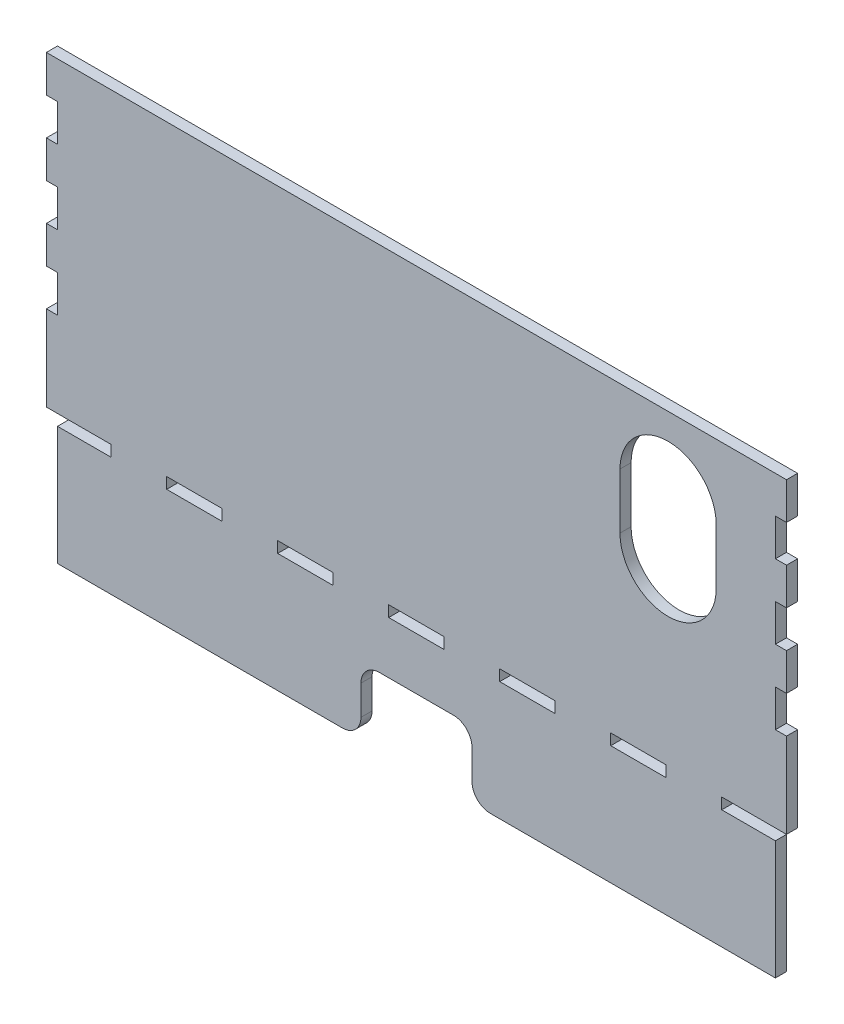
SolidWorks part; units mm, degrees
ref_plane "Front Plane" through (0, 0, 0) normal (0, 0, 1) x (1, 0, 0)
ref_plane "Top Plane" through (0, 0, 0) normal (0, 1, 0) x (1, 0, 0)
ref_plane "Right Plane" through (0, 0, 0) normal (1, 0, 0) x (0, 0, -1)
sketch "Sketch1" plane through (0, 0, 0) normal (0, 0, 1) x (1, 0, 0)
  line L0 (-97, 0) -> (97, 0) construction
  line L1 (0, -25.5) -> (0, 57.5) construction
  line L2 (100, -2.5) -> (97, -2.5)
  line L3 (-97, 57.5) -> (97, 57.5)
  line L4 (100, -25.5) -> (100, -2.5)
  line L5 (0, -25.5) -> (7.5, -25.5)
  line L6 (-97, -25.5) -> (-100, -25.5)
  line L7 (-100, -25.5) -> (-100, -2.5)
  line L8 (-97, 57.5) -> (-100, 57.5)
  line L9 (-100, 57.5) -> (-100, 47.5)
  line L10 (-100, 47.5) -> (-97, 47.5)
  line L11 (-97, 47.5) -> (-97, 37.5)
  line L12 (-97, 37.5) -> (-100, 37.5)
  line L13 (-100, 37.5) -> (-100, 27.5)
  line L14 (100, 17.5) -> (100, 7.5)
  line L15 (-100, 27.5) -> (-97, 27.5)
  line L16 (-97, 27.5) -> (-97, 17.5)
  line L17 (97, 7.5) -> (100, 7.5)
  line L18 (97, 17.5) -> (100, 17.5)
  line L19 (97, 7.5) -> (97, -2.5)
  line L20 (97, 27.5) -> (97, 17.5)
  line L21 (100, 27.5) -> (97, 27.5)
  line L22 (100, 37.5) -> (100, 27.5)
  line L23 (97, 37.5) -> (100, 37.5)
  line L24 (97, 47.5) -> (97, 37.5)
  line L25 (100, 47.5) -> (97, 47.5)
  line L26 (100, 57.5) -> (100, 47.5)
  line L27 (97, 57.5) -> (100, 57.5)
  line L28 (7.5, -25.5) -> (7.5, -28.5)
  line L29 (7.5, -28.5) -> (22.5, -28.5)
  line L30 (22.5, -28.5) -> (22.5, -25.5)
  line L31 (30, -25.5) -> (37.5, -25.5)
  line L32 (37.5, -25.5) -> (37.5, -28.5)
  line L33 (37.5, -28.5) -> (52.5, -28.5)
  line L34 (52.5, -28.5) -> (52.5, -25.5)
  line L35 (60, -25.5) -> (67.5, -25.5)
  line L36 (67.5, -25.5) -> (67.5, -28.5)
  line L37 (67.5, -28.5) -> (82.5, -28.5)
  line L38 (82.5, -28.5) -> (82.5, -25.5)
  line L39 (22.5, -25.5) -> (30, -25.5)
  line L40 (52.5, -25.5) -> (60, -25.5)
  line L41 (82.5, -25.5) -> (97, -25.5)
  line L42 (0, -25.5) -> (-7.5, -25.5)
  line L43 (-7.5, -25.5) -> (-7.5, -28.5)
  line L44 (-7.5, -28.5) -> (-22.5, -28.5)
  line L45 (-22.5, -28.5) -> (-22.5, -25.5)
  line L46 (-22.5, -25.5) -> (-37.5, -25.5)
  line L47 (-37.5, -25.5) -> (-37.5, -28.5)
  line L48 (-37.5, -28.5) -> (-52.5, -28.5)
  line L49 (-52.5, -28.5) -> (-52.5, -25.5)
  line L50 (-52.5, -25.5) -> (-67.5, -25.5)
  line L51 (-67.5, -25.5) -> (-67.5, -28.5)
  line L52 (-100, -2.5) -> (-97, -2.5)
  line L53 (97, -25.5) -> (100, -25.5)
  line L56 (-97, 7.5) -> (-97, -2.5)
  line L57 (-97, 17.5) -> (-100, 17.5)
  line L58 (-97, 7.5) -> (-100, 7.5)
  line L59 (-100, 17.5) -> (-100, 7.5)
  line L60 (-67.5, -28.5) -> (-82.5, -28.5)
  line L62 (-82.5, -28.5) -> (-82.5, -25.5)
  line L63 (-82.5, -25.5) -> (-97, -25.5)
  dimension "D2" = 7.5
  dimension "D4" = 83
  dimension "D5" = 10
  dimension "D6" = 194
  dimension "D8" = 7.5
  dimension "D9" = 15
  dimension "D10" = 3
  dimension "D11" = 10
  dimension "D7" = 10
  dimension "D13" = 10
  dimension "D12" = 10
  dimension "D14" = 7.5
  dimension "D15" = 14.5
  dimension "D16" = 10
  dimension "D18" = 3
  dimension "D19" = 15
  dimension "D20" = 15
  dimension "D21" = 15
  dimension "D22" = 15
  dimension "D23" = 15
extrude "Boss-Extrude1" add sketch "Sketch1" along normal blind 3
sketch "Sketch2" plane through (0, 0, 3) normal (0, 0, 1) x (1, 0, 0)
  line L0 (0, -25.5) -> (0, 22.5) construction
  line L1 (-7.5, -25.5) -> (7.5, -25.5) construction
  line L2 (0, 22.5) -> (68, 22.5) construction
  line L3 (68, 22.5) -> (68, 37.5) construction
  line L4 (55, 22.5) -> (55, 37.5)
  line L5 (81, 22.5) -> (81, 37.5)
  arc A0 (55, 22.5) -> (81, 22.5) centre (68, 22.5) ccw
  arc A1 (81, 37.5) -> (55, 37.5) centre (68, 37.5) ccw
  point P7 (68, 30)
  dimension "D4" = 13
  dimension "D1" = 48
  dimension "D2" = 68
  dimension "D3" = 15
extrude "Cut-Extrude1" cut sketch "Sketch2" against normal blind 10
sketch "Sketch3" plane through (0, -28.5, 0) normal (0, -1, 0) x (1, 0, 0)
  line L0 (-100, 3) -> (-82.5, 3) construction
  line L1 (-97, 3) -> (97, 3)
  line L2 (-97, 3) -> (-97, 0)
  line L3 (-97, 0) -> (97, 0)
  line L4 (97, 3) -> (97, 0)
  line L5 (82.5, 0) -> (100, 0) construction
  line L6 (-100, 3) -> (-100, 0) construction
  line L7 (100, 3) -> (100, 0) construction
  point P8 (-100, 1.5)
  point P11 (100, 1.5)
  dimension "D1" = 3
  dimension "D2" = 3
extrude "Boss-Extrude2" add sketch "Sketch3" along normal blind 32.11
sketch "Sketch4" plane through (0, 0, 3) normal (0, 0, 1) x (1, 0, 0)
  line L0 (0, -60.61) -> (0, -46.61) construction
  line L1 (97, -60.61) -> (-97, -60.61) construction
  line L3 (-15, -42.61) -> (15, -42.61)
  line L4 (-15, -42.61) -> (-15, -60.61)
  line L5 (-15, -60.61) -> (15, -60.61)
  line L6 (15, -42.61) -> (15, -60.61)
  dimension "D1" = 14
  dimension "D2" = 30
  dimension "D3" = 18
  dimension "D4" = 15
extrude "Cut-Extrude2" cut sketch "Sketch4" against normal blind 22
fillet "Fillet1" radius 5 2 edges at (15, -60.61, 1.5) (-15, -60.61, 1.5)
fillet "Fillet2" radius 5 2 edges at (15, -42.61, 1.5) (-15, -42.61, 1.5)
